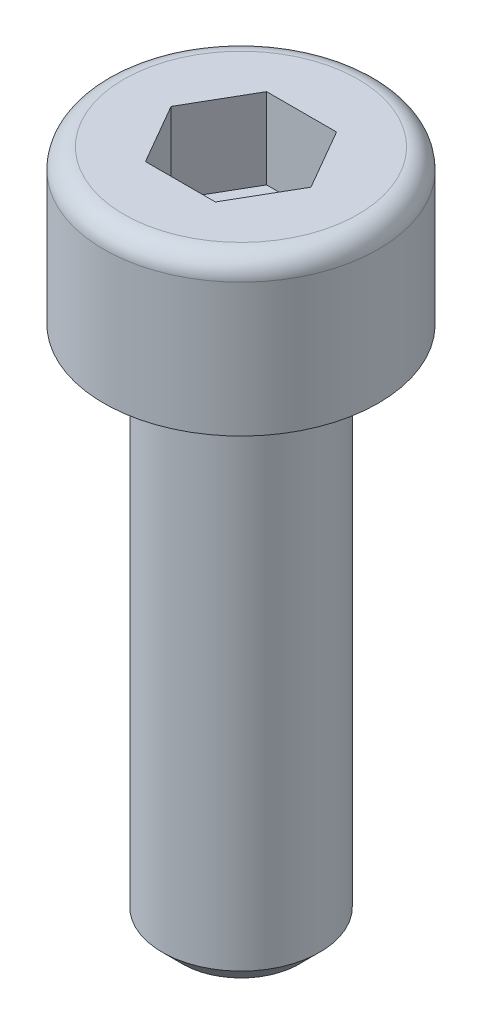
SolidWorks part; units mm, degrees
material "1023 Tôle d'acier au carbone (SS)"
ref_plane "Plan de face" through (0, 0, 0) normal (0, 0, 1) x (1, 0, 0)
ref_plane "Plan de dessus" through (0, 0, 0) normal (0, 1, 0) x (1, 0, 0)
ref_plane "Plan de droite" through (0, 0, 0) normal (1, 0, 0) x (0, 0, -1)
sketch "Esquisse1" plane through (0, 0, 0) normal (0, 0, 1) x (1, 0, 0)
  line L0 (0, 3.8) -> (0, -13) construction
  line L1 (0, 3.8) -> (-2.9, 3.8)
  line L2 (-3.4, 3.3) -> (-3.4, 0)
  line L3 (-3.4, 0) -> (-1.95, 0)
  line L4 (-1.95, 0) -> (-1.95, -12.5)
  line L5 (-1.95, -12.5) -> (-1.45, -13)
  line L6 (-1.45, -13) -> (0, -13)
  line L7 (0, 3.8) -> (0, -13)
  arc A0 (-2.9, 3.8) -> (-3.4, 3.3) centre (-2.9, 3.3) ccw
  point P11 (-1.95, -13)
  dimension "D5" = 0.5
  dimension "D1" = 3.9
  dimension "D2" = 6.8
  dimension "D3" = 13
  dimension "D4" = 3.8
  dimension "D8" = 0.5
revolve "Révolution1" add sketch "Esquisse1" angle 360 about L0
cosmetic thread "Représentation de filetage1" parameters "D2"=3.2
sketch "Esquisse2" plane through (0, 3.8, 0) normal (0, 1, 0) x (-1, 0, 0)
  line L1 (-1.7321, 0) -> (-0.866, -1.5)
  line L2 (-0.866, -1.5) -> (0.866, -1.5)
  line L3 (0.866, -1.5) -> (1.7321, 0)
  line L4 (1.7321, 0) -> (0.866, 1.5)
  line L5 (0.866, 1.5) -> (-0.866, 1.5)
  line L6 (-0.866, 1.5) -> (-1.7321, 0)
  circle A0 centre (0, 0) radius 1.5 construction
  dimension "D1" = 3
extrude "Enlèv. mat.-Extru.1" cut sketch "Esquisse2" against normal blind 2
